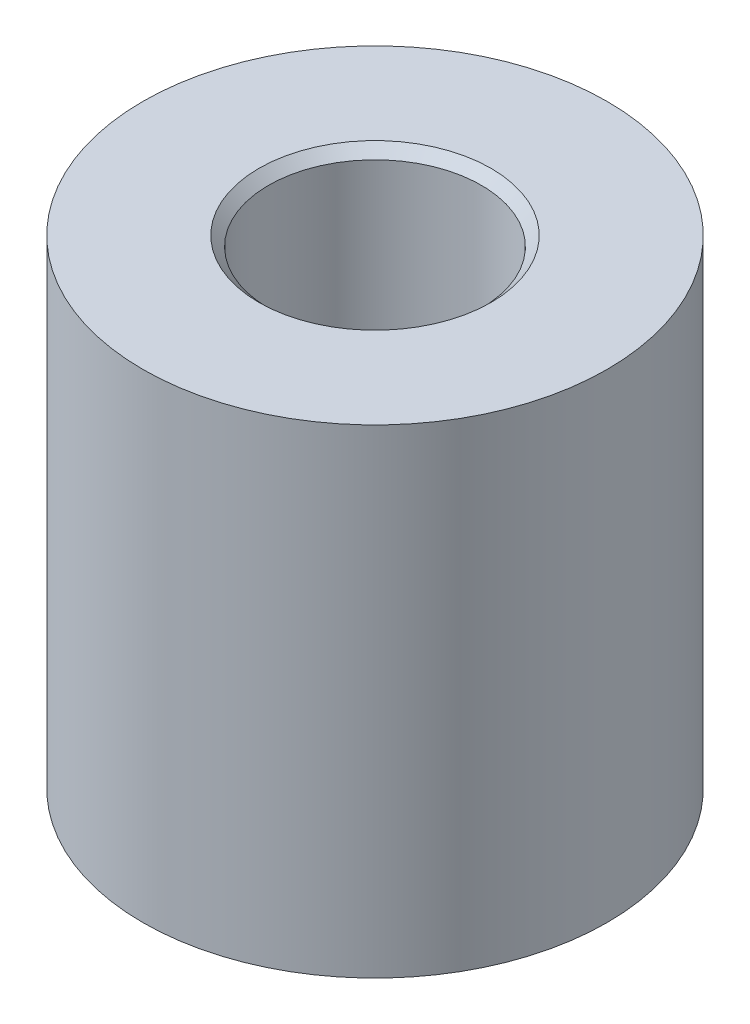
SolidWorks part; units mm, degrees
ref_plane "Front Plane" through (0, 0, 0) normal (0, 0, 1) x (1, 0, 0)
ref_plane "Top Plane" through (0, 0, 0) normal (0, 1, 0) x (1, 0, 0)
ref_plane "Right Plane" through (0, 0, 0) normal (1, 0, 0) x (0, 0, -1)
sketch "Sketch1" plane through (0, 0, 0) normal (0, 1, 0) x (1, 0, 0)
  circle A0 centre (0, 0) radius 4.7625
  circle A1 centre (0, 0) radius 2.1828
  dimension "D1" = 9.525
  dimension "D2" = 4.3656
extrude "Boss-Extrude1" add sketch "Sketch1" along normal blind 9.829
chamfer "Chamfer1" distance 0.2 angle 45 2 edges at (0, 0, 2.1828) (0, 9.829, 2.1828)
